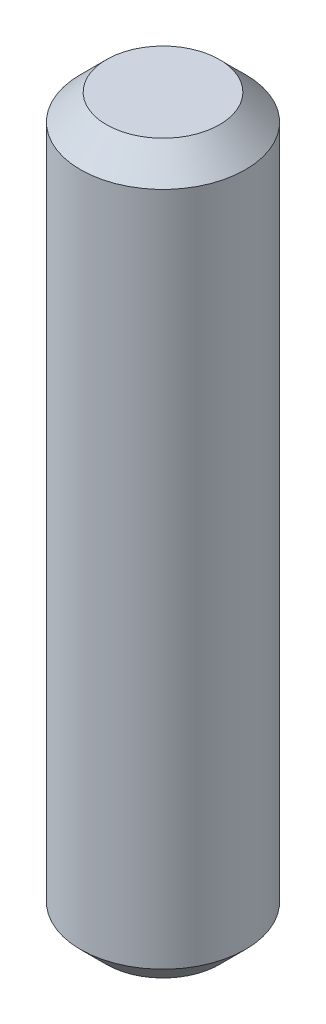
SolidWorks part; units mm, degrees
ref_plane "Спереди" through (0, 0, 0) normal (0, 0, 1) x (1, 0, 0)
ref_plane "Сверху" through (0, 0, 0) normal (0, 1, 0) x (1, 0, 0)
ref_plane "Справа" through (0, 0, 0) normal (1, 0, 0) x (0, 0, -1)
other "Configuration Table"
sketch "Эскиз1" plane through (0, 0, 0) normal (0, 1, 0) x (1, 0, 0)
  circle A0 centre (0, 0) radius 1.5875
  dimension "D1" = 3.175
extrude "Бобышка-Вытянуть1" add sketch "Эскиз1" along normal blind 14
chamfer "Фаска1" distance 0.5 angle 45 2 edges at (0, 0, 1.5875) (0, 14, 1.5875)
